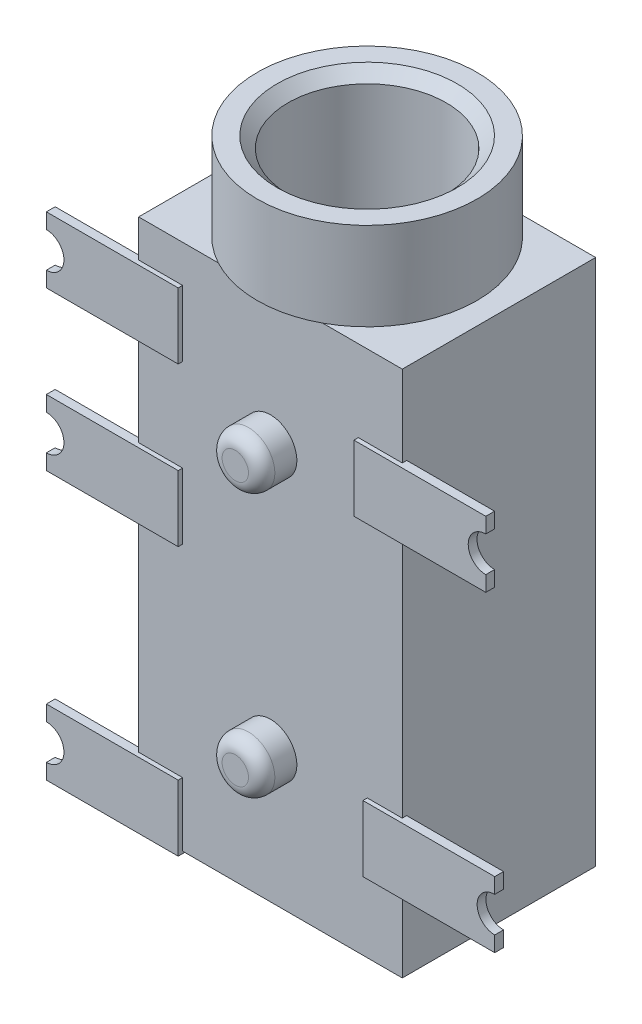
SolidWorks part; units mm, degrees
ref_plane "前视基准面" through (0, 0, 0) normal (0, 0, 1) x (1, 0, 0)
ref_plane "上视基准面" through (0, 0, 0) normal (0, 1, 0) x (1, 0, 0)
ref_plane "右视基准面" through (0, 0, 0) normal (1, 0, 0) x (0, 0, -1)
sketch "草图1" plane through (0, 0, 0) normal (0, 1, 0) x (1, 0, 0)
  line L1 (-3, 2.2) -> (3, 2.2)
  line L2 (-3, 2.2) -> (-3, -2.2)
  line L3 (-3, -2.2) -> (3, -2.2)
  line L4 (3, 2.2) -> (3, -2.2)
  line L5 (-3, 2.2) -> (3, -2.2) construction
  line L6 (-3, -2.2) -> (3, 2.2) construction
  point P0 (0, 0)
  dimension "D1" = 6
  dimension "D2" = 4.4
extrude "凸台-拉伸1" add sketch "草图1" along normal blind 12
sketch "草图2" plane through (0, 12, 0) normal (0, 1, 0) x (1, 0, 0)
  circle A0 centre (0, 0) radius 2.5
  dimension "D1" = 5
extrude "凸台-拉伸2" add sketch "草图2" along normal blind 2
sketch "草图3" plane through (0, 14, 0) normal (0, 1, 0) x (1, 0, 0)
  circle A0 centre (0, 0) radius 1.8
  dimension "D1" = 3.6
extrude "切除-拉伸1" cut sketch "草图3" against normal blind 13
sketch "草图5" plane through (0, 0, 2.2) normal (0, 0, 1) x (1, 0, 0)
  line L0 (0, 12) -> (0, 0) construction
  line L1 (-1.1874, 12) -> (1.1874, 12) construction
  line L2 (-3, 0) -> (3, 0) construction
  line L3 (1.1874, 12) -> (3, 12) construction
  line L4 (-5, 11.15) -> (-2, 11.15)
  line L5 (-5, 11.15) -> (-5, 9.65)
  line L6 (-5, 9.65) -> (-2, 9.65)
  line L7 (-2, 11.15) -> (-2, 9.65)
  line L8 (-3, 12) -> (-1.1874, 12) construction
  line L10 (-5, 7.55) -> (-2, 7.55)
  line L11 (-5, 7.55) -> (-5, 6.05)
  line L12 (-5, 6.05) -> (-2, 6.05)
  line L13 (-2, 7.55) -> (-2, 6.05)
  line L14 (-5, 1.45) -> (-2, 1.45)
  line L15 (-5, 1.45) -> (-5, -0.05)
  line L16 (-5, -0.05) -> (-2, -0.05)
  line L17 (-2, 1.45) -> (-2, -0.05)
  line L18 (2, 10.15) -> (5, 10.15)
  line L19 (2, 10.15) -> (2, 8.65)
  line L20 (2, 8.65) -> (5, 8.65)
  line L21 (5, 10.15) -> (5, 8.65)
  line L22 (2.2033, 3.15) -> (5.2033, 3.15)
  line L23 (2.2033, 3.15) -> (2.2033, 1.65)
  line L24 (2.2033, 1.65) -> (5.2033, 1.65)
  line L25 (5.2033, 3.15) -> (5.2033, 1.65)
  point P12 (-2, 10.4)
  point P29 (-2, 6.8)
  point P30 (-2, 0.7)
  point P31 (3, 12)
  point P32 (2, 9.4)
  point P34 (2.2033, 2.4)
  dimension "D1" = 2
  dimension "D2" = 1.5
  dimension "D3" = 3
  dimension "D4" = 1.6
  dimension "D5" = 6.1
  dimension "D6" = 5.2
  dimension "D7" = 2
  dimension "D8" = 7
  dimension "D9" = 1.85
extrude "凸台-拉伸3" add sketch "草图5" along normal blind 0.1 and the other way blind 0.1 separate body
sketch "草图6" plane through (0, 0, 2.3) normal (0, 0, 1) x (1, 0, 0)
  line L0 (-5, 11.15) -> (-5, 9.65) construction
  line L1 (5, 8.65) -> (5, 10.15) construction
  line L2 (-5, 7.55) -> (-5, 6.05) construction
  line L3 (5.2033, 1.65) -> (5.2033, 3.15) construction
  line L4 (-5, 1.45) -> (-5, -0.05) construction
  circle A0 centre (-5, 10.4) radius 0.4
  circle A1 centre (-5, 6.8) radius 0.4
  circle A2 centre (5, 9.4) radius 0.4
  circle A3 centre (5.2033, 2.4) radius 0.4
  circle A4 centre (-5, 0.7) radius 0.4
  point P0 (-5, 10.4)
  point P1 (5, 9.4)
  point P4 (-5, 6.8)
  point P7 (5.2033, 2.4)
  point P10 (-5, 0.7)
  dimension "D1" = 0.8
extrude "切除-拉伸2" cut sketch "草图6" against normal up to next (0.2 mm away)
chamfer "倒角1" distance 0.25 angle 45 1 edges at (0, 14, 1.8)
sketch "草图7" plane through (0, 0, 2.2) normal (0, 0, 1) x (1, 0, 0)
  line L0 (0, 12) -> (0, 0) construction
  line L1 (-1.1874, 12) -> (1.1874, 12) construction
  circle A0 centre (0, 9) radius 0.6
  circle A1 centre (0, 3) radius 0.6
  dimension "D1" = 1.2
  dimension "D2" = 3
  dimension "D3" = 6
extrude "凸台-拉伸4" add sketch "草图7" along normal blind 0.8
fillet "圆角1" radius 0.3 2 edges at (0.6, 3, 3) (0.6, 9, 3)
